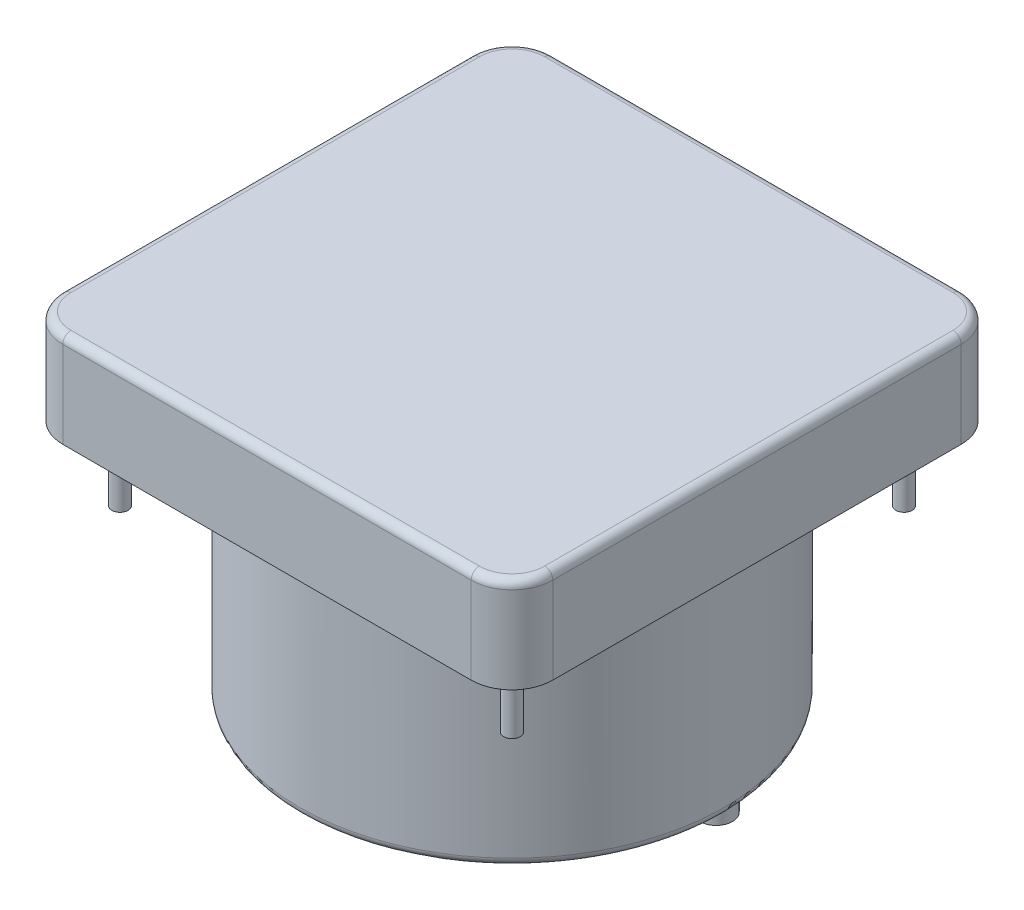
SolidWorks part; units mm, degrees
ref_plane "Front Plane" through (0, 0, 0) normal (0, 0, 1) x (1, 0, 0)
ref_plane "Top Plane" through (0, 0, 0) normal (0, 1, 0) x (1, 0, 0)
ref_plane "Right Plane" through (0, 0, 0) normal (1, 0, 0) x (0, 0, -1)
sketch "Sketch1" plane through (0, 0, 0) normal (0, 1, 0) x (1, 0, 0)
  circle A0 centre (0, 0) radius 26
  dimension "D1" = 52
extrude "Boss-Extrude1" add sketch "Sketch1" along normal blind 29
sketch "Sketch2" plane through (0, 29, 0) normal (0, 1, 0) x (1, 0, 0)
  line L1 (-30, -30) -> (30, -30)
  line L2 (-30, -30) -> (-30, 30)
  line L3 (-30, 30) -> (30, 30)
  line L4 (30, -30) -> (30, 30)
  line L5 (-30, -30) -> (30, 30) construction
  line L6 (-30, 30) -> (30, -30) construction
  point P0 (0, 0)
  dimension "D1" = 60
  dimension "D2" = 60
extrude "Boss-Extrude2" add sketch "Sketch2" along normal blind 11.6
fillet "Fillet1" radius 5 4 edges at (-30, 34.8, -30) (-30, 34.8, 30) (30, 34.8, -30) (30, 34.8, 30)
sketch "Sketch5" plane through (0, 0, 0) normal (0, -1, 0) x (1, 0, 0)
  line L0 (0, -14.8305) -> (0, 14.2344) construction
  line L1 (18.8272, 0) -> (-18.0595, 0) construction
  circle A0 centre (15, -10) radius 2
  circle A1 centre (-15, -10) radius 2
  dimension "D1" = 4
  dimension "D2" = 15
  dimension "D3" = 10
extrude "Boss-Extrude3" add sketch "Sketch5" along normal blind 10
sketch "Sketch6" plane through (0, 29, 0) normal (0, -1, 0) x (1, 0, 0)
  line L0 (0, -34.921) -> (0, 40.0901) construction
  line L1 (36.063, 0) -> (-45.5596, 0) construction
  line L2 (25, -30) -> (-25, -30) construction
  line L3 (30, 25) -> (30, -25) construction
  circle A0 centre (24, -24) radius 1
  circle A1 centre (24, 24) radius 1
  circle A2 centre (-24, 24) radius 1
  circle A3 centre (-24, -24) radius 1
  dimension "D1" = 2
  dimension "D2" = 6
  dimension "D3" = 6
extrude "Boss-Extrude4" add sketch "Sketch6" along normal blind 9
fillet "Fillet2" radius 1 8 edges at (-28.5355, 40.6, -28.5355) (0, 40.6, -30) (28.5355, 40.6, -28.5355) (30, 40.6, 0) (28.5355, 40.6, 28.5355) (0, 40.6, 30) (-28.5355, 40.6, 28.5355) (-30, 40.6, 0)
fillet "Fillet3" radius 1 1 edges at (0, 0, 26)
sketch "Sketch7" plane through (0, 0, 0) normal (0, -1, 0) x (1, 0, 0)
  line L0 (0, -15.5892) -> (0, 9.7723) construction
  circle A0 centre (15, -10) radius 5
  circle A1 centre (-15, -10) radius 5
  dimension "D1" = 10
extrude "Boss-Extrude5" add sketch "Sketch7" along normal blind 1
